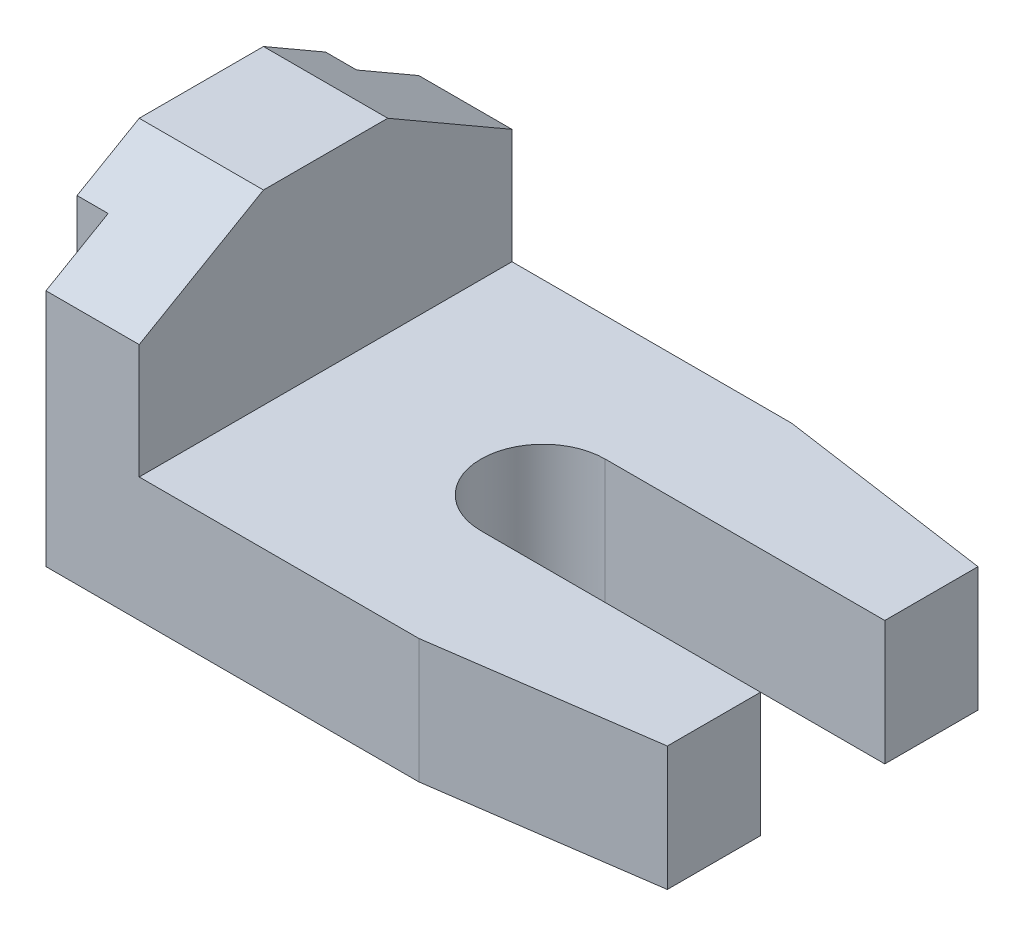
SolidWorks part; units mm, degrees
ref_plane "前视基准面" through (0, 0, 0) normal (0, 0, 1) x (1, 0, 0)
ref_plane "上视基准面" through (0, 0, 0) normal (0, 1, 0) x (1, 0, 0)
ref_plane "右视基准面" through (0, 0, 0) normal (1, 0, 0) x (0, 0, -1)
sketch "草图2" plane through (0, 0, 0) normal (0, 1, 0) x (1, 0, 0)
  line L0 (0, 0) -> (0, 38.1)
  line L1 (0, 38.1) -> (57.15, 38.1)
  line L2 (57.15, 38.1) -> (101.6, 31.75)
  line L3 (101.6, 31.75) -> (101.6, 12.7)
  line L4 (101.6, 12.7) -> (44.45, 12.7)
  line L5 (44.45, -12.7) -> (101.6, -12.7)
  line L6 (101.6, -31.75) -> (57.15, -38.1)
  line L7 (57.15, -38.1) -> (0, -38.1)
  line L8 (0, -38.1) -> (0, 0)
  line L9 (101.6, -12.7) -> (101.6, -31.75)
  arc A0 (44.45, 12.7) -> (44.45, -12.7) centre (44.45, 0) ccw
  point P13 (0, 0)
  point P14 (101.3163, -35.4012)
  point P15 (101.9404, -33.6054)
  point P16 (0, 0)
  dimension "D1" = 12.7
  dimension "D2" = 101.6
  dimension "D3" = 44.45
  dimension "D4" = 6.35
  dimension "D5" = 57.15
  dimension "D6" = 76.2
extrude "凸台-拉伸1" add sketch "草图2" along normal blind 25.4
sketch "草图4" plane through (0, 0, 0) normal (0, -1, 0) x (-1, 0, 0)
  line L0 (0, 38.1) -> (0, -38.1)
  line L1 (0, -38.1) -> (19.05, -38.1)
  line L2 (19.05, -38.1) -> (19.05, -25.4)
  line L3 (19.05, -25.4) -> (25.4, -25.4)
  line L4 (25.4, -25.4) -> (25.4, 25.4)
  line L5 (25.4, 25.4) -> (19.05, 25.4)
  line L6 (19.05, 25.4) -> (19.05, 38.1)
  line L7 (19.05, 38.1) -> (0, 38.1)
  point P10 (25.4, 25.4)
  point P12 (0, 0)
  dimension "D1" = 12.7
  dimension "D2" = 6.35
  dimension "D3" = 25.4
extrude "凸台-拉伸2" add sketch "草图4" against normal blind 63.5
sketch "草图5" plane through (0, 0, 0) normal (1, 0, 0) x (0, 0, -1)
  line L0 (-38.1, 63.5) -> (-38.1, 48.8353)
  line L1 (-38.1, 63.5) -> (-38.1, 25.4) construction
  line L2 (-38.1, 48.8353) -> (-12.7, 63.5)
  line L3 (38.1, 63.5) -> (-38.1, 63.5) construction
  line L4 (-12.7, 63.5) -> (-38.1, 63.5)
  line L5 (38.1, 63.5) -> (12.7, 63.5)
  line L6 (12.7, 63.5) -> (38.1, 48.8353)
  line L7 (38.1, 63.5) -> (38.1, 25.4) construction
  line L8 (38.1, 48.8353) -> (38.1, 63.5)
  dimension "D1" = 30
  dimension "D2" = 25.4
extrude "切除-拉伸1" cut sketch "草图5" against normal blind 63.5
